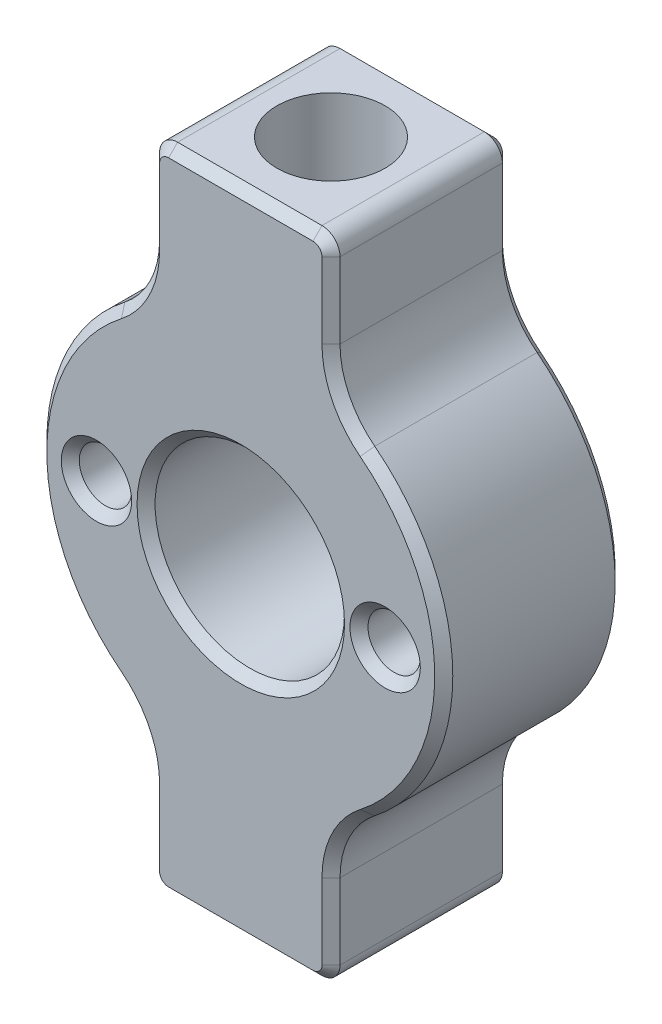
SolidWorks part; units mm, degrees
ref_plane "Front" through (0, 0, 0) normal (0, 0, 1) x (1, 0, 0)
ref_plane "Top" through (0, 0, 0) normal (0, 1, 0) x (1, 0, 0)
ref_plane "Right" through (0, 0, 0) normal (1, 0, 0) x (0, 0, -1)
sketch "Skizze1" plane through (0, 0, 0) normal (0, 0, 1) x (1, 0, 0)
  circle A0 centre (0, 0) radius 5.25
  circle A1 centre (0, 0) radius 11.25
  dimension "D1" = 10.5
  dimension "D2" = 6
extrude "Aufsatz-Linear austragen1" add sketch "Skizze1" along normal blind 10
sketch "Skizze2" plane through (0, 0, 0) normal (0, 1, 0) x (1, 0, 0)
  line L0 (0, 0) -> (0, -10) construction
  line L3 (-11.25, -10) -> (11.25, -10) construction
  line L4 (5.25, 0) -> (-5.25, 0) construction
  line L5 (-5, -10) -> (5, -10)
  line L6 (-5, -10) -> (-5, 0)
  line L7 (-5, 0) -> (5, 0)
  line L8 (5, -10) -> (5, 0)
  line L9 (-5, -10) -> (5, 0) construction
  line L10 (-5, 0) -> (5, -10) construction
  point P4 (0, -5)
extrude "Aufsatz-Linear austragen2" add sketch "Skizze2" along normal blind 12 from offset 6
sketch "Skizze3" plane through (0, 18, 0) normal (0, 1, 0) x (1, 0, 0)
  line L0 (0, 0) -> (0, -10) construction
  line L1 (-5, -10) -> (5, -10) construction
  circle A0 centre (0, -5) radius 3
  dimension "D1" = 6
extrude "Schnitt-Linear austragen1" cut sketch "Skizze3" against normal blind 10
mirror "Spiegeln1" about plane through (0, 0, 0) normal (0, 1, 0) of "Schnitt-Linear austragen1", "Aufsatz-Linear austragen2"
sketch "Skizze4" plane through (0, 0, 10) normal (0, 0, 1) x (1, 0, 0)
  line L0 (0, 0) -> (0, 11.1324) construction
  line L1 (0, 0) -> (13.0739, 0) construction
  circle A2 centre (8, 0) radius 1.45
  circle A3 centre (-8, 0) radius 1.45
  dimension "D1" = 16
  dimension "D2" = 2.9
extrude "Schnitt-Linear austragen2" cut sketch "Skizze4" against normal blind 8
fillet "Verrundung2" radius 5 4 edges at (-5, -10.0778, 5) (-5, 10.0778, 5) (5, 10.0778, 5) (5, -10.0778, 5)
fillet "Verrundung1" radius 1 4 edges at (-5, 18, 5) (5, 18, 5) (5, -18, 5) (-5, -18, 5)
chamfer "Fase1" distance 0.5 angle 45 36 edges at (-5, 14.9043, 10) (-5, -14.9043, 10) (0, -18, 10) (5, -14.9043, 10) (5, 14.9043, 10) (-4.7071, -17.7071, 10) (4.7071, -17.7071, 10) (4.7071, 17.7071, 10) (-4.7071, 17.7071, 10) (-5, 14.9043, 0) (5, -14.9043, 0) (0, -18, 0) (-5, -14.9043, 0) (5, 14.9043, 0) (-4.7071, -17.7071, 0) (4.7071, -17.7071, 0) (4.7071, 17.7071, 0) (-4.7071, 17.7071, 0) (5.25, 0, 0) (5.25, 0, 10) (9.45, 0, 10) (-9.45, 0, 10) (-11.25, 0, 0) (-11.25, 0, 10) (11.25, 0, 10) (11.25, 0, 0) (-5.5064, -10.616, 10) (-5.5064, -10.616, 0) (-5.5064, 10.616, 10) (-5.5064, 10.616, 0) (5.5064, 10.616, 0) (5.5064, 10.616, 10) (5.5064, -10.616, 0) (5.5064, -10.616, 10) (0, 18, 0) (0, 18, 10)
